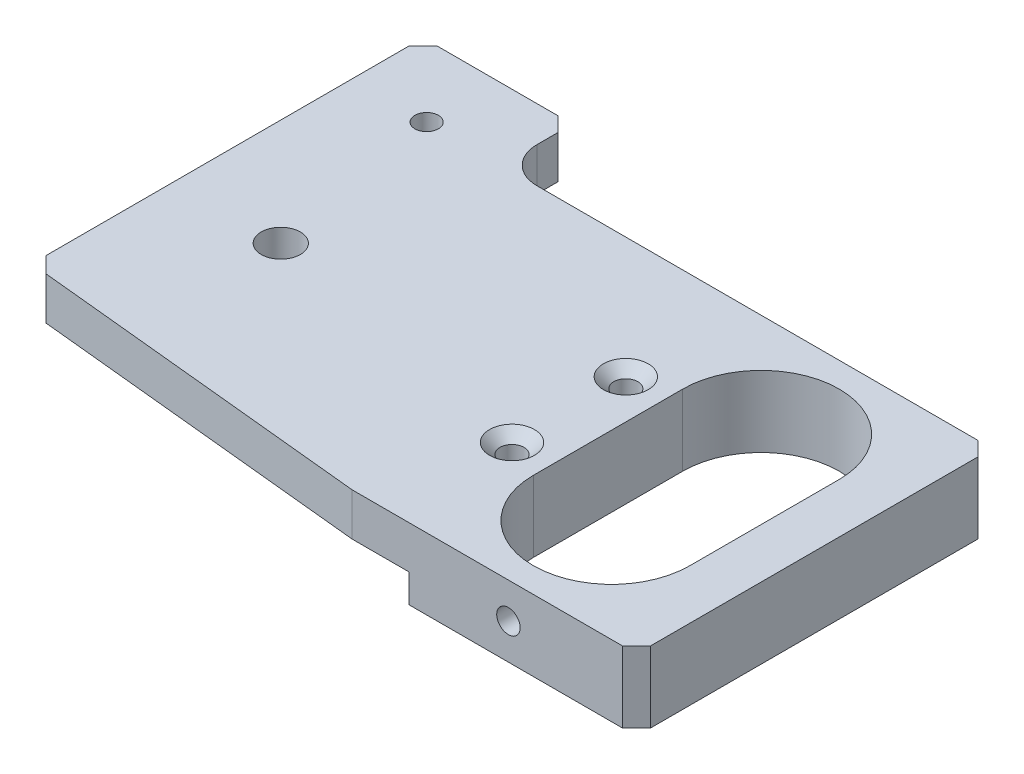
SolidWorks part; units mm, degrees
material "1060 Legierung"
ref_plane "Ebene vorne" through (0, 0, 0) normal (0, 0, 1) x (1, 0, 0)
ref_plane "Ebene oben" through (0, 0, 0) normal (0, 1, 0) x (1, 0, 0)
ref_plane "Ebene rechts" through (0, 0, 0) normal (1, 0, 0) x (0, 0, -1)
sketch "Skizze1" plane through (0, 0, 0) normal (0, 1, 0) x (1, 0, 0)
  line L0 (-50, 35) -> (-29, 35)
  line L1 (40, 25) -> (-29, 25)
  line L2 (-50, -20) -> (-50, 35)
  line L3 (-29, 25) -> (-29, 35)
  line L4 (40, -25) -> (40, 25)
  line L6 (-50, -20) -> (0, -25)
  line L7 (0, -25) -> (40, -25)
  point P0 (0, 0)
  point P11 (40, 0)
  dimension "D1" = 50
  dimension "D2" = 40
  dimension "D3" = 90
  dimension "D4" = 55
  dimension "D5" = 5
  dimension "D6" = 21
extrude "Aufsatz-Linear austragen1" add sketch "Skizze1" along normal blind 6
sketch "Skizze8" plane through (0, 0, 0) normal (0, -1, 0) x (1, 0, 0)
  line L0 (8, 25) -> (40, 25)
  line L1 (8, 25) -> (8, -25)
  line L3 (40, 25) -> (40, -25)
  line L4 (8, -25) -> (40, -25)
  dimension "D1" = 32
extrude "Aufsatz-Linear austragen2" add sketch "Skizze8" along normal blind 4
sketch "Skizze4" plane through (0, 6, 0) normal (0, 1, 0) x (1, 0, 0)
  line L0 (11, 10.5) -> (11, -10.5)
  line L1 (33, -10.5) -> (33, 10.5)
  line L2 (0, 0) -> (40, 0) construction
  line L3 (40, -25) -> (40, 25) construction
  line L4 (40, -25) -> (40, 25) construction
  arc A0 (11, -10.5) -> (33, -10.5) centre (22, -10.5) ccw
  arc A1 (33, 10.5) -> (11, 10.5) centre (22, 10.5) ccw
  point P7 (22, -21.5)
  point P8 (22, 21.5)
  dimension "D1" = 43
  dimension "D2" = 22
  dimension "D3" = 18
extrude "Schnitt-Linear austragen1" cut sketch "Skizze4" against normal through all
hole_wizard "Stirnsenkung für M5 Flachkopfschraube mit Schlitz2" positions "Skizze13" profile "Skizze14" counterbore size "M5" standard "DIN"
sketch "Skizze13" plane through (0, 0, 0) normal (0, -1, 0) x (-1, 0, 0)
  line L0 (50, 35) -> (50, -20) construction
  point P21 (35, 0)
  dimension "D1" = 15
sketch "Skizze14" plane through (-35, 0, 0) normal (1, 0, 0) x (0, 0, -1)
  line L0 (0, 0) -> (0, 21.6524)
  line L1 (0, 21.6524) -> (2.75, 20)
  line L2 (2.75, 20) -> (2.75, 1.7)
  line L3 (2.75, 1.7) -> (5.5, 1.7)
  line L4 (5.5, 1.7) -> (5.5, 0)
  line L5 (5.5, 0) -> (0, 0)
  line L10 (0, 21.6524) -> (-2.75, 20) construction
  line L11 (0, -6.35) -> (0, 107.95) construction
  dimension "Bohrerdurchmesser" = 5.5
  dimension "Bohrungstiefe" = 20
  dimension "Senkdurchmesser2" = 11
  dimension "Senktiefe2" = 1.7
  dimension "Spitzenwinkel" = 118
sketch "Skizze24" plane through (0, 0, 25) normal (0, 0, 1) x (1, 0, 0)
  line L0 (40, 6) -> (40, -4) construction
  line L1 (40, 1) -> (0, 1) construction
  line L2 (0, 6) -> (0, 0) construction
  circle A0 centre (37, 1) radius 1.7
  dimension "D1" = 3.4
  dimension "D2" = 3
extrude "Schnitt-Linear austragen5" [suppressed] cut sketch "Skizze24" against normal blind 20
hole_wizard "M3 Gewindebohrung2" [suppressed] positions "Skizze25" profile "Skizze26" tap size "M3" standard "DIN"
sketch "Skizze25" [suppressed] plane through (0, 0, 5) normal (0, 0, 1) x (1, 0, 0)
  point P0 (37, 1)
sketch "Skizze26" plane through (37, 1, 5) normal (1, 0, 0) x (0, -1, 0)
  line L0 (0, 0) -> (0, 9.2511)
  line L1 (0, 9.2511) -> (1.25, 8.5)
  line L2 (1.25, 8.5) -> (1.25, 0)
  line L5 (1.25, 0) -> (0, 0)
  line L10 (0, 9.2511) -> (-1.25, 8.5) construction
  line L11 (0, -6.35) -> (0, 107.95) construction
  dimension "Bohrerdurchmesser" = 2.5
  dimension "Bohrungstiefe" = 8.5
  dimension "Spitzenwinkel" = 118
cosmetic thread "Bohrungsgewinde2" [suppressed] parameters "D1"=6, "D2"=3
sketch "Skizze15" plane through (0, 6, 0) normal (0, 1, 0) x (1, 0, 0)
  line L0 (40, -10.5) -> (40, -9.3)
  line L2 (40, -9.3) -> (33, -9.3)
  line L3 (33, -9.3) -> (33, -10.5)
  line L4 (33, -10.5) -> (40, -10.5)
  line L7 (40, -25) -> (40, 25) construction
  line L8 (33, -10.5) -> (33, 10.5) construction
  dimension "D3" = 1.2
extrude "Schnitt-Linear austragen3" [suppressed] cut sketch "Skizze15" against normal through all
hole_wizard "Formsenkung für M3 Linsensenkschraube mit Schlitz1" positions "Skizze22" profile "Skizze23" countersink size "M3" standard "DIN"
sketch "Skizze22" plane through (0, 6, 0) normal (0, 1, 0) x (1, 0, 0)
  line L0 (0, 0) -> (-23.9573, 0) construction
  point P0 (5.5, 8)
  point P2 (5.5, -8)
  dimension "D1" = 16
  dimension "D2" = 5.5
sketch "Skizze23" plane through (5.5, 6, -8) normal (1, 0, 0) x (0, 0, 1)
  line L0 (0, 0) -> (0, 9.5215)
  line L1 (0, 9.5215) -> (1.7, 8.5)
  line L2 (1.7, 8.5) -> (1.7, 1.45)
  line L3 (1.7, 1.45) -> (3.15, 0)
  line L5 (3.15, 0) -> (0, 0)
  line L6 (-1.7, 1.45) -> (-3.15, 0) construction
  line L10 (0, 9.5215) -> (-1.7, 8.5) construction
  line L11 (0, -6.35) -> (0, 107.95) construction
  dimension "Bohrerdurchmesser" = 3.4
  dimension "Bohrungstiefe" = 8.5
  dimension "Senkdurchmesser (Oben)" = 6.3
  dimension "Senkwinkel (Oben)" = 90
  dimension "Spitzenwinkel" = 118
chamfer "Fase1" distance 2 angle 45 5 edges at (40, 1, 25) (40, 1, -25) (-50, 3, 20) (-50, 3, -35) (-29, 3, -35)
fillet "Verrundung1" radius 5 1 edges at (-29, 3, -25)
hole_wizard "M4 Gewindebohrung1" positions "Skizze27" profile "Skizze28" tap size "M4" standard "DIN" end condition through all
sketch "Skizze27" plane through (0, 6, 0) normal (0, 1, 0) x (1, 0, 0)
  line L0 (-31, 35) -> (-48, 35) construction
  point P0 (-39.5, 25)
  point P6 (-39.5, 35)
  dimension "D1" = 10
sketch "Skizze28" plane through (-39.5, 6, -25) normal (1, 0, 0) x (0, 0, 1)
  line L0 (0, 0) -> (0, 10)
  line L1 (0, 10) -> (1.65, 10)
  line L2 (1.65, 10) -> (1.65, 0)
  line L5 (1.65, 0) -> (0, 0)
  line L11 (0, -6.35) -> (0, 107.95) construction
  dimension "Bohrerdurchmesser" = 3.3
  dimension "Bohrungstiefe" = 10
cosmetic thread "Bohrungsgewinde3" parameters "D2"=4
hole_wizard "M4 Gewindebohrung2" positions "Skizze29" profile "Skizze30" tap size "M4" standard "DIN"
sketch "Skizze29" plane through (0, 0, 25) normal (0, 0, 1) x (1, 0, 0)
  line L3 (0, 6) -> (0, 0) construction
  line L4 (40, 1) -> (-2.603, 1) construction
  line L5 (40, 6) -> (40, -4) construction
  point P0 (22, 1)
  dimension "D1" = 22
sketch "Skizze30" plane through (22, 1, 25) normal (1, 0, 0) x (0, -1, 0)
  line L0 (0, 0) -> (0, 3.5)
  line L1 (0, 3.5) -> (1.65, 3.5)
  line L2 (1.65, 3.5) -> (1.65, 0)
  line L5 (1.65, 0) -> (0, 0)
  line L11 (0, -6.35) -> (0, 107.95) construction
  dimension "Bohrerdurchmesser" = 3.3
  dimension "Bohrungstiefe" = 3.5
cosmetic thread "Bohrungsgewinde4" parameters "D2"=4
